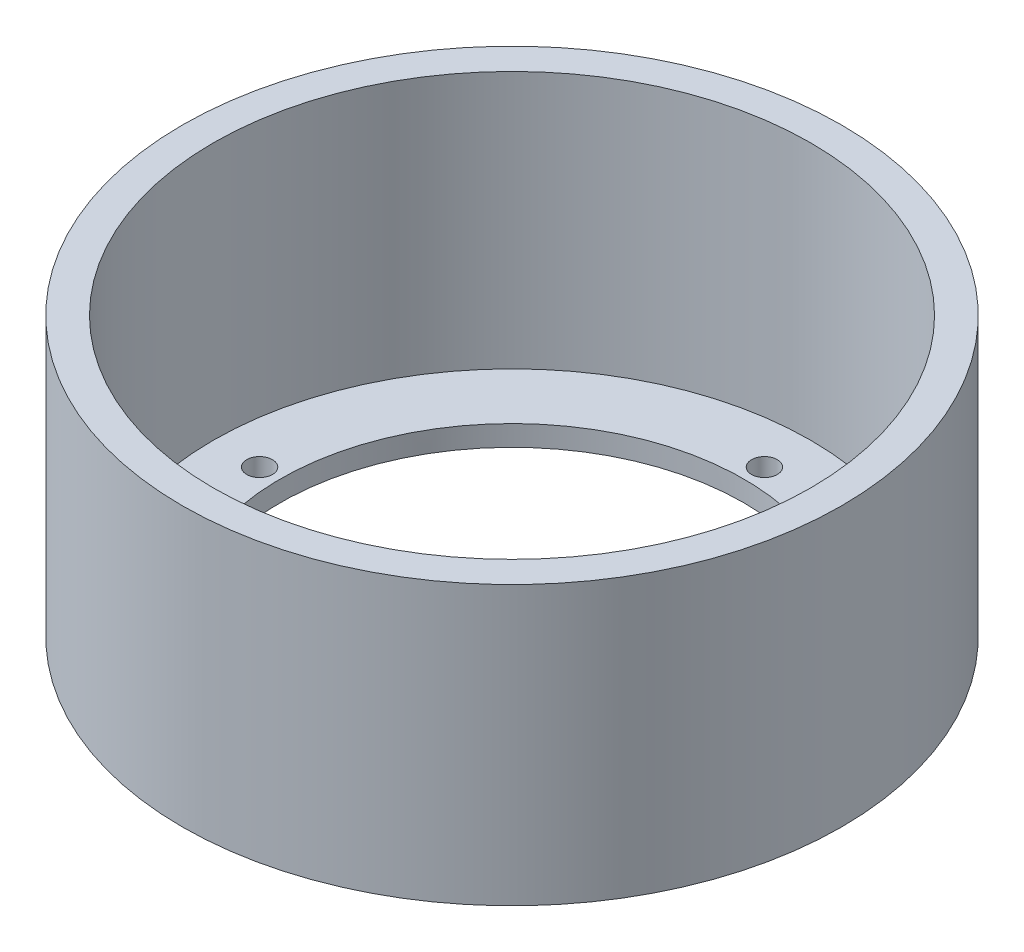
SolidWorks part; units mm, degrees
ref_plane "前视基准面" through (0, 0, 0) normal (0, 0, 1) x (1, 0, 0)
ref_plane "上视基准面" through (0, 0, 0) normal (0, 1, 0) x (1, 0, 0)
ref_plane "右视基准面" through (0, 0, 0) normal (1, 0, 0) x (0, 0, -1)
sketch "草图1" plane through (0, 0, 0) normal (0, 1, 0) x (1, 0, 0)
  circle A0 centre (0, 0) radius 32
  dimension "D1" = 64
extrude "凸台-拉伸1" add sketch "草图1" along normal blind 27
cosmetic thread "装饰螺纹线2" parameters "D1"=14, "D2"=57.505
ref_plane "基准面2" through (0, 5, 0) normal (0, -1, 0) x (-1, 0, 0)
sketch "草图5" plane through (0, 5, 0) normal (0, -1, 0) x (-1, 0, 0)
  circle A0 centre (0, 0) radius 22.5
  dimension "D1" = 45
extrude "切除-拉伸3" cut sketch "草图5" along normal through all and the other way through all
ref_plane "基准面3" through (0, 27, 0) normal (0, 1, 0) x (1, 0, 0)
sketch "草图6" plane through (0, 27, 0) normal (0, 1, 0) x (1, 0, 0)
  circle A0 centre (0, 0) radius 29
  dimension "D1" = 58
extrude "切除-拉伸4" cut sketch "草图6" against normal blind 25 contours A0
ref_plane "基准面4" through (0, 0, 0) normal (0, 1, 0) x (1, 0, 0)
ref_plane "定位面" through (0, 2, 0) normal (0, 1, 0) x (1, 0, 0)
sketch "草图7" plane through (0, 0, 0) normal (0, 1, 0) x (1, 0, 0)
  circle A0 centre (0, 0) radius 24.5
hole_wizard "M3 螺纹孔1" positions "草图10" profile "草图11" tap size "M3" standard "GB" end condition through all
sketch "草图10" plane through (0, 0, 0) normal (0, -1, 0) x (-1, 0, 0)
  line L1 (0, 0) -> (24.5, 0) construction
  line L2 (24.5, 0) -> (35.5596, 0) construction
  line L4 (0, 0) -> (0, 33.9658) construction
  line L6 (0, 0) -> (0, -34.472) construction
  line L8 (0, 0) -> (-38.4132, 0) construction
  line L9 (0, 0) -> (0, -34.4675) construction
  circle A0 centre (0, 0) radius 24.5 construction
  point P0 (24.5, 0)
  point P31 (0, 24.5)
  point P33 (-24.5, 0)
  point P35 (0, -24.5)
  dimension "D1" = 90
sketch "草图11" plane through (-24.5, 0, 0) normal (1, 0, 0) x (0, 0, -1)
  line L0 (0, 0) -> (0, 27)
  line L1 (0, 27) -> (1.25, 27)
  line L2 (1.25, 27) -> (1.25, 0)
  line L5 (1.25, 0) -> (0, 0)
  line L11 (0, -6.35) -> (0, 107.95) construction
  dimension "通孔螺纹孔钻头直径" = 2.5
  dimension "通孔螺纹孔钻头深度" = 27
cosmetic thread "孔螺蚊线2" parameters "D2"=3
cosmetic thread "孔螺蚊线3" parameters "D2"=3
cosmetic thread "孔螺蚊线4" parameters "D2"=3
cosmetic thread "孔螺蚊线5" parameters "D2"=3
